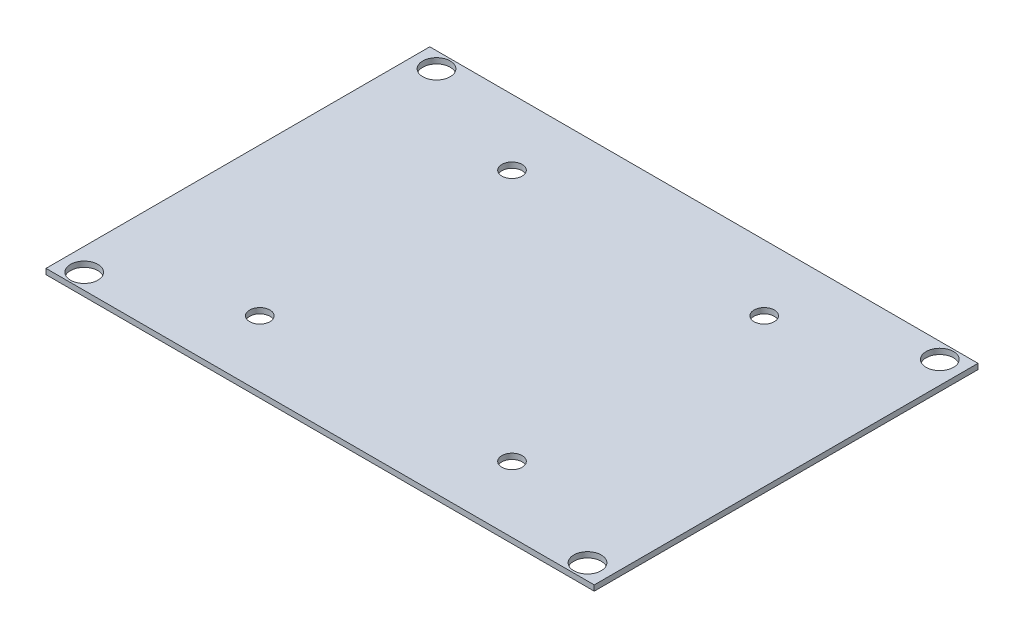
SolidWorks part; units mm, degrees
ref_plane "Alzado" through (0, 0, 0) normal (0, 0, 1) x (1, 0, 0)
ref_plane "Planta" through (0, 0, 0) normal (0, 1, 0) x (1, 0, 0)
ref_plane "Vista lateral" through (0, 0, 0) normal (1, 0, 0) x (0, 0, -1)
sketch "Croquis4" plane through (0, 0, 0) normal (0, 1, 0) x (1, 0, 0)
  line L1 (-50, 35) -> (50, 35)
  line L2 (-50, 35) -> (-50, -35)
  line L3 (-50, -35) -> (50, -35)
  line L4 (50, 35) -> (50, -35)
  line L5 (-50, 35) -> (50, -35) construction
  line L6 (-50, -35) -> (50, 35) construction
  line L11 (-23, 23) -> (23, -23) construction
  line L12 (-23, -23) -> (23, 23) construction
  circle A0 centre (-23, 23) radius 1.85
  circle A1 centre (-23, -23) radius 1.85
  circle A2 centre (23, -23) radius 1.85
  circle A3 centre (23, 23) radius 1.85
  circle A4 centre (-45.9038, 32.1327) radius 2.5
  circle A5 centre (45.9038, 32.1327) radius 2.5
  circle A6 centre (45.9038, -32.1327) radius 2.5
  circle A7 centre (-45.9038, -32.1327) radius 2.5
  point P0 (0, 0)
  point P6 (0, 0)
  dimension "D5" = 3.7
  dimension "D6" = 3.7
  dimension "D7" = 3.7
  dimension "D8" = 3.7
  dimension "D10" = 5
  dimension "D11" = 5
  dimension "D12" = 5
  dimension "D13" = 5
  dimension "D1" = 100
  dimension "D2" = 70
  dimension "D3" = 46
  dimension "D4" = 46
  dimension "D9" = 5
  dimension "D14" = 5
  dimension "D15" = 5
  dimension "D16" = 5
extrude "Saliente-Extruir3" add sketch "Croquis4" along normal blind 1
